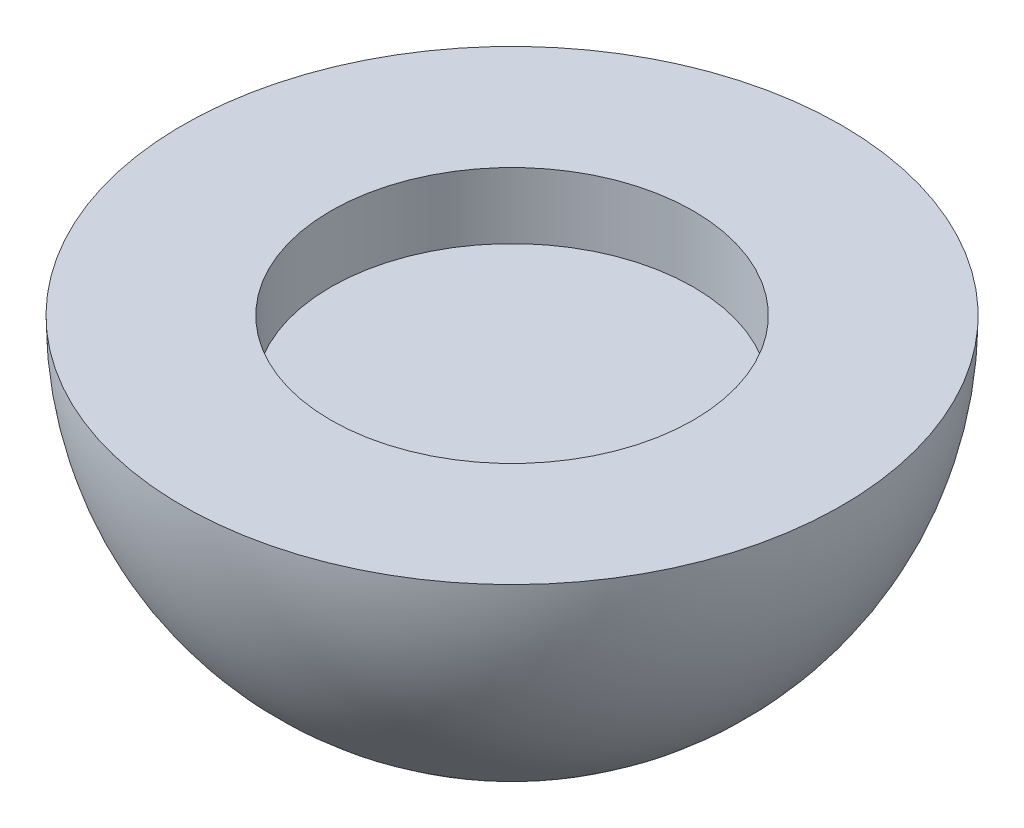
SolidWorks part; units mm, degrees
ref_plane "Front" through (0, 0, 0) normal (0, 0, 1) x (1, 0, 0)
ref_plane "Top" through (0, 0, 0) normal (0, 1, 0) x (1, 0, 0)
ref_plane "Right" through (0, 0, 0) normal (1, 0, 0) x (0, 0, -1)
sketch "Sketch1" plane through (0, 0, 0) normal (0, 1, 0) x (1, 0, 0)
  line L0 (5, 0) -> (-5, 0)
  arc A0 (5, 0) -> (-5, 0) centre (0, 0) ccw
  dimension "D1" = 10
revolve "Revolve1" add sketch "Sketch1" angle 180 about L0
sketch "Sketch3" plane through (0, 0, 0) normal (0, 1, 0) x (1, 0, 0)
  circle A0 centre (0, 0) radius 2.75
  dimension "D1" = 5.5
extrude "Cut-Extrude1" cut sketch "Sketch3" against normal blind 1
